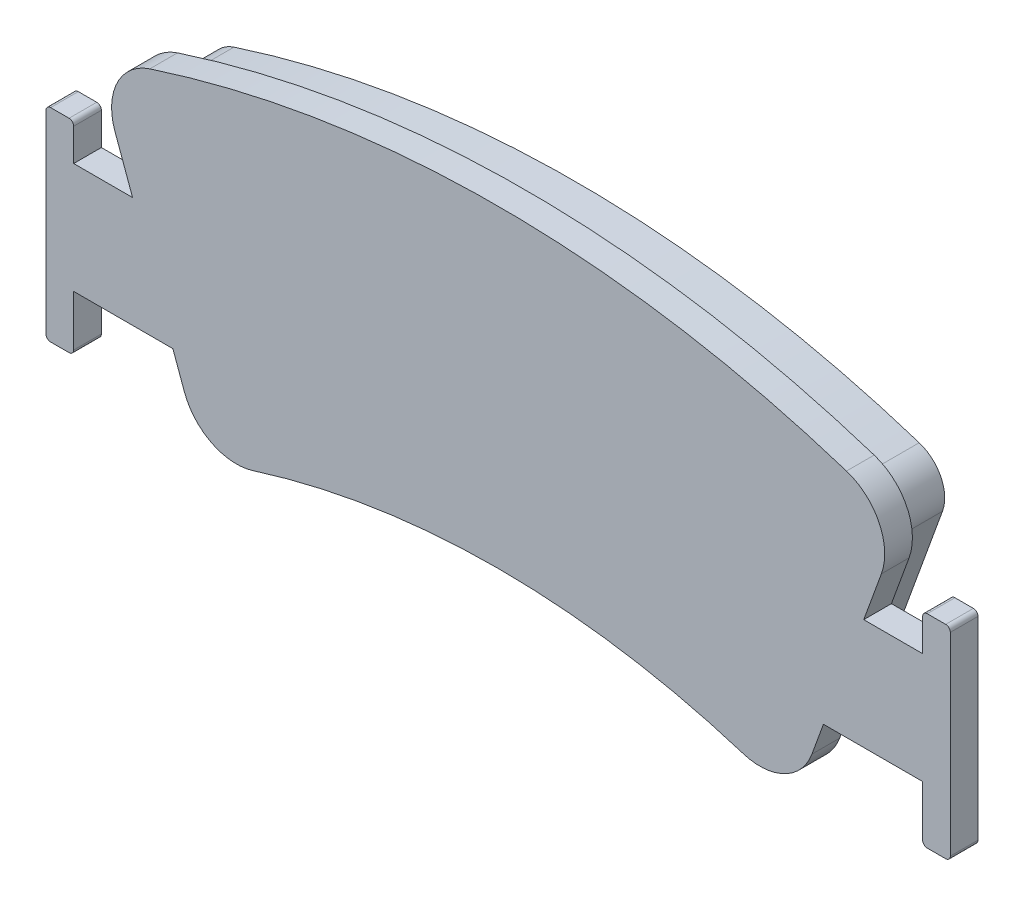
SolidWorks part; units mm, degrees
ref_plane "Płaszczyzna przednia" through (0, 0, 0) normal (0, 0, 1) x (1, 0, 0)
ref_plane "Płaszczyzna górna" through (0, 0, 0) normal (0, 1, 0) x (1, 0, 0)
ref_plane "Płaszczyzna prawa" through (0, 0, 0) normal (1, 0, 0) x (0, 0, -1)
sketch "Szkic1" plane through (0, 0, 0) normal (0, 0, 1) x (1, 0, 0)
  line L0 (-3.3117, 84.9355) -> (-2.9977, 76.8831)
  line L1 (0.9603, 74.1578) -> (23.3617, 81.7266)
  line L2 (57.7167, 62.4002) -> (52.2449, 56.4843)
  line L3 (53.1165, 51.7585) -> (74.3086, 41.2702)
  line L4 (84.9355, 3.3117) -> (76.8831, 2.9977)
  line L5 (74.1578, -0.9603) -> (81.7266, -23.3617)
  line L6 (62.4002, -57.7167) -> (56.4843, -52.2449)
  line L7 (51.7585, -53.1165) -> (41.2702, -74.3086)
  line L8 (3.3117, -84.9355) -> (2.9977, -76.8831)
  line L9 (-0.9603, -74.1578) -> (-23.3617, -81.7266)
  line L10 (-57.7167, -62.4002) -> (-52.2449, -56.4843)
  line L11 (-53.1165, -51.7585) -> (-74.3086, -41.2702)
  line L12 (-84.9355, -3.3117) -> (-76.8831, -2.9977)
  line L13 (-74.1578, 0.9603) -> (-81.7266, 23.3617)
  line L14 (-62.4002, 57.7167) -> (-56.4843, 52.2449)
  line L15 (-51.7585, 53.1165) -> (-41.2702, 74.3086)
  line L16 (0.9603, 74.1578) -> (-1.6342, 73.1454)
  line L17 (-2.9977, 74.077) -> (-2.9977, 76.8831)
  line L18 (53.1165, 51.7585) -> (50.5661, 52.8772)
  line L19 (50.2606, 54.5001) -> (52.2449, 56.4843)
  line L20 (74.1578, -0.9603) -> (73.1454, 1.6342)
  line L21 (74.077, 2.9977) -> (76.8831, 2.9977)
  line L22 (51.7585, -53.1165) -> (52.8772, -50.5661)
  line L23 (54.5001, -50.2606) -> (56.4843, -52.2449)
  line L24 (-0.9603, -74.1578) -> (1.6342, -73.1454)
  line L25 (2.9977, -74.077) -> (2.9977, -76.8831)
  line L26 (-53.1165, -51.7585) -> (-50.5661, -52.8772)
  line L27 (-50.2606, -54.5001) -> (-52.2449, -56.4843)
  line L28 (-74.1578, 0.9603) -> (-73.1454, -1.6342)
  line L29 (-74.077, -2.9977) -> (-76.8831, -2.9977)
  line L30 (-51.7585, 53.1165) -> (-52.8772, 50.5661)
  line L31 (-54.5001, 50.2606) -> (-56.4843, 52.2449)
  line L32 (-3.2338, 82.937) -> (-2.9977, 76.8831)
  line L33 (19.9378, 80.5697) -> (15.0444, 78.9164)
  line L34 (0.9603, 74.1578) -> (5.5705, 75.7155)
  line L35 (44.0396, 59.8465) -> (26.6236, 49.8436)
  line L36 (22.133, 52.2992) -> (21.2067, 71.3197)
  line L37 (25.5267, 74.1578) -> (43.8691, 65.1401)
  line L38 (70.4876, 34.3874) -> (77.0812, 15.0409)
  line L39 (73.4586, 11.1771) -> (54.0705, 16.4191)
  line L40 (52.6315, 21.3307) -> (65.426, 35.4352)
  line L41 (74.1578, -25.5267) -> (65.1401, -43.8691)
  line L42 (59.8465, -44.0396) -> (49.8436, -26.6236)
  line L43 (52.2992, -22.133) -> (71.3197, -21.2067)
  line L44 (34.3874, -70.4876) -> (15.0409, -77.0812)
  line L45 (11.1771, -73.4586) -> (16.4191, -54.0705)
  line L46 (21.3307, -52.6315) -> (35.4352, -65.426)
  line L47 (-25.5267, -74.1578) -> (-43.8691, -65.1401)
  line L48 (-44.0396, -59.8465) -> (-26.6236, -49.8436)
  line L49 (-22.133, -52.2992) -> (-21.2067, -71.3197)
  line L50 (-70.4876, -34.3874) -> (-77.0812, -15.0409)
  line L51 (-73.4586, -11.1771) -> (-54.0705, -16.4191)
  line L52 (-52.6315, -21.3307) -> (-65.426, -35.4352)
  line L53 (-74.1578, 25.5267) -> (-65.1401, 43.8691)
  line L54 (-59.8465, 44.0396) -> (-49.8436, 26.6236)
  line L55 (-52.2992, 22.133) -> (-71.3197, 21.2067)
  line L56 (-34.3874, 70.4876) -> (-15.0409, 77.0812)
  line L57 (-11.1771, 73.4586) -> (-16.4191, 54.0705)
  line L58 (-21.3307, 52.6315) -> (-35.4352, 65.426)
  circle A0 centre (0, 0) radius 120
  arc A2 (-62.4002, 57.7167) -> (-81.7266, 23.3617) centre (0, 0) ccw
  circle A3 centre (0, 50) radius 7
  circle A4 centre (50, 0) radius 7
  circle A5 centre (0, -50) radius 7
  circle A6 centre (-50, 0) radius 7
  circle A7 centre (0, 0) radius 35
  circle A8 centre (10.3075, 77.316) radius 5
  circle A9 centre (61.9591, 47.3822) radius 5
  circle A10 centre (77.316, -10.3075) radius 5
  circle A11 centre (47.3822, -61.9591) radius 5
  circle A12 centre (-10.3075, -77.316) radius 5
  circle A13 centre (-61.9591, -47.3822) radius 5
  circle A14 centre (-77.316, 10.3075) radius 5
  circle A15 centre (-47.3822, 61.9591) radius 5
  arc A16 (-2.9977, 76.8831) -> (0.9603, 74.1578) centre (0, 77) ccw
  arc A17 (52.2449, 56.4843) -> (53.1165, 51.7585) centre (54.4472, 54.4472) ccw
  arc A18 (76.8831, 2.9977) -> (74.1578, -0.9603) centre (77, 0) ccw
  arc A19 (56.4843, -52.2449) -> (51.7585, -53.1165) centre (54.4472, -54.4472) ccw
  arc A20 (2.9977, -76.8831) -> (-0.9603, -74.1578) centre (0, -77) ccw
  arc A21 (-52.2449, -56.4843) -> (-53.1165, -51.7585) centre (-54.4472, -54.4472) ccw
  arc A22 (-76.8831, -2.9977) -> (-74.1578, 0.9603) centre (-77, 0) ccw
  arc A23 (-56.4843, 52.2449) -> (-51.7585, 53.1165) centre (-54.4472, 54.4472) ccw
  arc A24 (-84.9355, -3.3117) -> (-74.3086, -41.2702) centre (0, 0) ccw
  arc A25 (-57.7167, -62.4002) -> (-23.3617, -81.7266) centre (0, 0) ccw
  arc A26 (3.3117, -84.9355) -> (41.2702, -74.3086) centre (0, 0) ccw
  arc A27 (62.4002, -57.7167) -> (81.7266, -23.3617) centre (0, 0) ccw
  arc A28 (84.9355, 3.3117) -> (74.3086, 41.2702) centre (0, 0) ccw
  arc A29 (57.7167, 62.4002) -> (23.3617, 81.7266) centre (0, 0) ccw
  arc A30 (-3.3117, 84.9355) -> (-41.2702, 74.3086) centre (0, 0) ccw
  arc A31 (19.9378, 80.5697) -> (56.3587, 60.9319) centre (0, 0) cw
  arc A32 (-1.6342, 73.1454) -> (-2.9977, 74.077) centre (-1.9977, 74.077) cw
  arc A33 (50.5661, 52.8772) -> (50.2606, 54.5001) centre (50.9678, 53.793) cw
  arc A34 (71.0696, 42.8732) -> (82.937, 3.2338) centre (0, 0) cw
  arc A35 (73.1454, 1.6342) -> (74.077, 2.9977) centre (74.077, 1.9977) cw
  arc A36 (80.5697, -19.9378) -> (60.9319, -56.3587) centre (0, 0) cw
  arc A37 (52.8772, -50.5661) -> (54.5001, -50.2606) centre (53.793, -50.9678) cw
  arc A38 (42.8732, -71.0696) -> (3.2338, -82.937) centre (0, 0) cw
  arc A39 (1.6342, -73.1454) -> (2.9977, -74.077) centre (1.9977, -74.077) cw
  arc A40 (-19.9378, -80.5697) -> (-56.3587, -60.9319) centre (0, 0) cw
  arc A41 (-50.5661, -52.8772) -> (-50.2606, -54.5001) centre (-50.9678, -53.793) cw
  arc A42 (-71.0696, -42.8732) -> (-82.937, -3.2338) centre (0, 0) cw
  arc A43 (-73.1454, -1.6342) -> (-74.077, -2.9977) centre (-74.077, -1.9977) cw
  arc A44 (-80.5697, 19.9378) -> (-60.9319, 56.3587) centre (0, 0) cw
  arc A45 (-52.8772, 50.5661) -> (-54.5001, 50.2606) centre (-53.793, 50.9678) cw
  arc A46 (-42.8732, 71.0696) -> (-3.2338, 82.937) centre (0, 0) cw
  arc A47 (15.0444, 78.9164) -> (5.5705, 75.7155) centre (10.3075, 77.316) ccw
  arc A48 (44.0396, 59.8465) -> (43.8691, 65.1401) centre (42.5455, 62.4479) ccw
  arc A49 (21.2067, 71.3197) -> (25.5267, 74.1578) centre (24.2031, 71.4656) cw
  arc A50 (26.6236, 49.8436) -> (22.133, 52.2992) centre (25.1294, 52.4451) cw
  arc A51 (65.426, 35.4352) -> (70.4876, 34.3874) centre (67.648, 33.4196) cw
  arc A52 (73.4586, 11.1771) -> (77.0812, 15.0409) centre (74.2416, 14.0731) ccw
  arc A53 (54.0705, 16.4191) -> (52.6315, 21.3307) centre (54.8535, 19.3151) cw
  arc A54 (71.3197, -21.2067) -> (74.1578, -25.5267) centre (71.4656, -24.2031) cw
  arc A55 (59.8465, -44.0396) -> (65.1401, -43.8691) centre (62.4479, -42.5455) ccw
  arc A56 (49.8436, -26.6236) -> (52.2992, -22.133) centre (52.4451, -25.1294) cw
  arc A57 (35.4352, -65.426) -> (34.3874, -70.4876) centre (33.4196, -67.648) cw
  arc A58 (11.1771, -73.4586) -> (15.0409, -77.0812) centre (14.0731, -74.2416) ccw
  arc A59 (16.4191, -54.0705) -> (21.3307, -52.6315) centre (19.3151, -54.8535) cw
  arc A60 (-21.2067, -71.3197) -> (-25.5267, -74.1578) centre (-24.2031, -71.4656) cw
  arc A61 (-44.0396, -59.8465) -> (-43.8691, -65.1401) centre (-42.5455, -62.4479) ccw
  arc A62 (-26.6236, -49.8436) -> (-22.133, -52.2992) centre (-25.1294, -52.4451) cw
  arc A63 (-65.426, -35.4352) -> (-70.4876, -34.3874) centre (-67.648, -33.4196) cw
  arc A64 (-73.4586, -11.1771) -> (-77.0812, -15.0409) centre (-74.2416, -14.0731) ccw
  arc A65 (-54.0705, -16.4191) -> (-52.6315, -21.3307) centre (-54.8535, -19.3151) cw
  arc A66 (-71.3197, 21.2067) -> (-74.1578, 25.5267) centre (-71.4656, 24.2031) cw
  arc A67 (-59.8465, 44.0396) -> (-65.1401, 43.8691) centre (-62.4479, 42.5455) ccw
  arc A68 (-49.8436, 26.6236) -> (-52.2992, 22.133) centre (-52.4451, 25.1294) cw
  arc A69 (-35.4352, 65.426) -> (-34.3874, 70.4876) centre (-33.4196, 67.648) cw
  arc A70 (-11.1771, 73.4586) -> (-15.0409, 77.0812) centre (-14.0731, 74.2416) ccw
  arc A71 (-16.4191, 54.0705) -> (-21.3307, 52.6315) centre (-19.3151, 54.8535) cw
  dimension "D1" = 240
  dimension "D2" = 14
  dimension "D3" = 170
  dimension "D5" = 70
  dimension "D6" = 10
  dimension "D10" = 77
  dimension "D12" = 3
  dimension "D11" = 2
  dimension "D14" = 1
  dimension "D16" = 3
  dimension "D4" = 4
  dimension "D7" = 50
  dimension "D8" = 78
  dimension "D9" = 8
  dimension "D13" = 8
  dimension "D15" = 8
  dimension "D17" = 8
sketch "Szkic2" plane through (0, 0, 0) normal (0, 0, 1) x (1, 0, 0)
  line L0 (0, 0) -> (-49.4404, 135.8364)
  line L1 (0, 0) -> (0, 158.8834)
  line L2 (-39.6507, 108.9395) -> (-32.1208, 88.2511)
  line L3 (0, 120) -> (0, 90)
  arc A0 (-35.9121, 98.6677) -> (0, 105) centre (0, 0) cw construction
  arc A1 (0, 120) -> (-37.1296, 114.1113) centre (0, 0) ccw
  arc A2 (0, 90) -> (-27.1551, 85.8056) centre (0, 0) ccw
  circle A5 centre (0, 0) radius 120 construction
  arc A6 (-27.1551, 85.8056) -> (-32.1208, 88.2511) centre (-28.362, 89.6192) cw
  arc A7 (-37.1296, 114.1113) -> (-39.6507, 108.9395) centre (-35.892, 110.3076) ccw
  point P6 (-18.2331, 103.4048)
  dimension "D4" = 105
  dimension "D5" = 4
  dimension "D1" = 20
  dimension "D2" = 30
  dimension "D3" = 20
extrude "Dodanie-wyciągnięcie1" add sketch "Szkic2" along normal blind 6.5 contours A1 A7 L0 A6 A2 L1
sketch "Szkic3" plane through (0, 0, 6.5) normal (0, 0, 1) x (1, 0, 0)
  line L0 (-35.2496, 91) -> (-34.0002, 87.5671)
  line L2 (-49, 103) -> (-49, 85.5)
  line L3 (-48.5, 85) -> (-46.5, 85)
  line L4 (-46, 85.5) -> (-46, 91)
  line L5 (-46, 91) -> (-35.2496, 91)
  line L7 (-41.5301, 108.2555) -> (-39.6173, 103)
  line L9 (-39.6507, 108.9395) -> (-32.1208, 88.2511)
  line L10 (0, 90) -> (0, 120)
  line L12 (0, 90) -> (0, 120)
  line L13 (0, 120) -> (0, 122)
  line L14 (0, 122) -> (0, 88)
  line L15 (-39.6507, 108.9395) -> (-32.1208, 88.2511) construction
  line L16 (2, 87.9773) -> (2, 121.9836) construction
  line L17 (-39.6173, 103) -> (-46, 103)
  line L18 (-41.5301, 108.2555) -> (-34.0002, 87.5671) construction
  line L19 (-49, 103) -> (-49, 106.5)
  line L20 (-48.5, 107) -> (-46.5, 107)
  line L21 (-46, 106.5) -> (-46, 103)
  arc A0 (0, 122) -> (-37.7485, 116.0132) centre (0, 0) ccw
  arc A1 (-37.7485, 116.0132) -> (-41.5301, 108.2555) centre (-35.892, 110.3076) ccw
  arc A2 (-34.0002, 87.5671) -> (-26.5517, 83.8988) centre (-28.362, 89.6192) ccw
  arc A3 (0, 88) -> (-26.5517, 83.8988) centre (0, 0) ccw
  arc A4 (0, 120) -> (-37.1296, 114.1113) centre (0, 0) ccw
  arc A5 (-37.1296, 114.1113) -> (-39.6507, 108.9395) centre (-35.892, 110.3076) ccw
  arc A6 (-32.1208, 88.2511) -> (-27.1551, 85.8056) centre (-28.362, 89.6192) ccw
  arc A7 (0, 90) -> (-27.1551, 85.8056) centre (0, 0) ccw
  arc A12 (2, 121.9836) -> (-37.7485, 116.0132) centre (0, 0) ccw construction
  arc A13 (2, 87.9773) -> (-26.5517, 83.8988) centre (0, 0) ccw construction
  arc A14 (0, 90) -> (-27.1551, 85.8056) centre (0, 0) ccw construction
  arc A15 (-32.1208, 88.2511) -> (-27.1551, 85.8056) centre (-28.362, 89.6192) ccw construction
  arc A16 (-37.1296, 114.1113) -> (-39.6507, 108.9395) centre (-35.892, 110.3076) ccw construction
  arc A17 (0, 120) -> (-37.1296, 114.1113) centre (0, 0) ccw construction
  arc A18 (-46.5, 85) -> (-46, 85.5) centre (-46.5, 85.5) ccw
  arc A19 (-49, 85.5) -> (-48.5, 85) centre (-48.5, 85.5) ccw
  arc A20 (-46.5, 107) -> (-46, 106.5) centre (-46.5, 106.5) cw
  arc A21 (-49, 106.5) -> (-48.5, 107) centre (-48.5, 106.5) cw
  point P33 (-46, 85)
  point P36 (-49, 85)
  point P41 (-49, 107)
  arc M13 (0, 120) -> (-37.1296, 114.1113) centre (0, 0) ccw
  arc M14 (-37.1296, 114.1113) -> (-39.6507, 108.9395) centre (-35.892, 110.3076) ccw
  line M15 (-39.6507, 108.9395) -> (-32.1208, 88.2511)
  arc M16 (-32.1208, 88.2511) -> (-27.1551, 85.8056) centre (-28.362, 89.6192) ccw
  arc M17 (-27.1551, 85.8056) -> (0, 90) centre (0, 0) cw
  line M18 (0, 90) -> (0, 120)
  dimension "D10" = 0.5
  dimension "D3" = 12
  dimension "D4" = 6
  dimension "D5" = 3
  dimension "D6" = 18
  dimension "D7" = 49
  dimension "D8" = 17
  dimension "D9" = 4
  dimension "D1" = 0
  dimension "D2" = 2
extrude "Dodanie-wyciągnięcie2" add sketch "Szkic3" along normal blind 3 contours M18 M13 M14 M15 M16 M17 | A3 L14 L13 A0 A1 L7 L17 L2 L3 L4 L5 L0 A2 M17 M16 M15 M14 M13
mirror "Lustro1" about plane through (0, 0, 0) normal (1, 0, 0) of "Dodanie-wyciągnięcie2", "Dodanie-wyciągnięcie1"
chamfer "Sfazowanie1" distance 1 angle 70 8 edges at (35.8858, 98.5953, 0) (30.1292, 86.0307, 0) (39.4875, 112.0603, 0) (0, 90, 0) (0, 120, 0) (-30.1292, 86.0307, 0) (-39.4875, 112.0603, 0) (-35.8858, 98.5953, 0)
